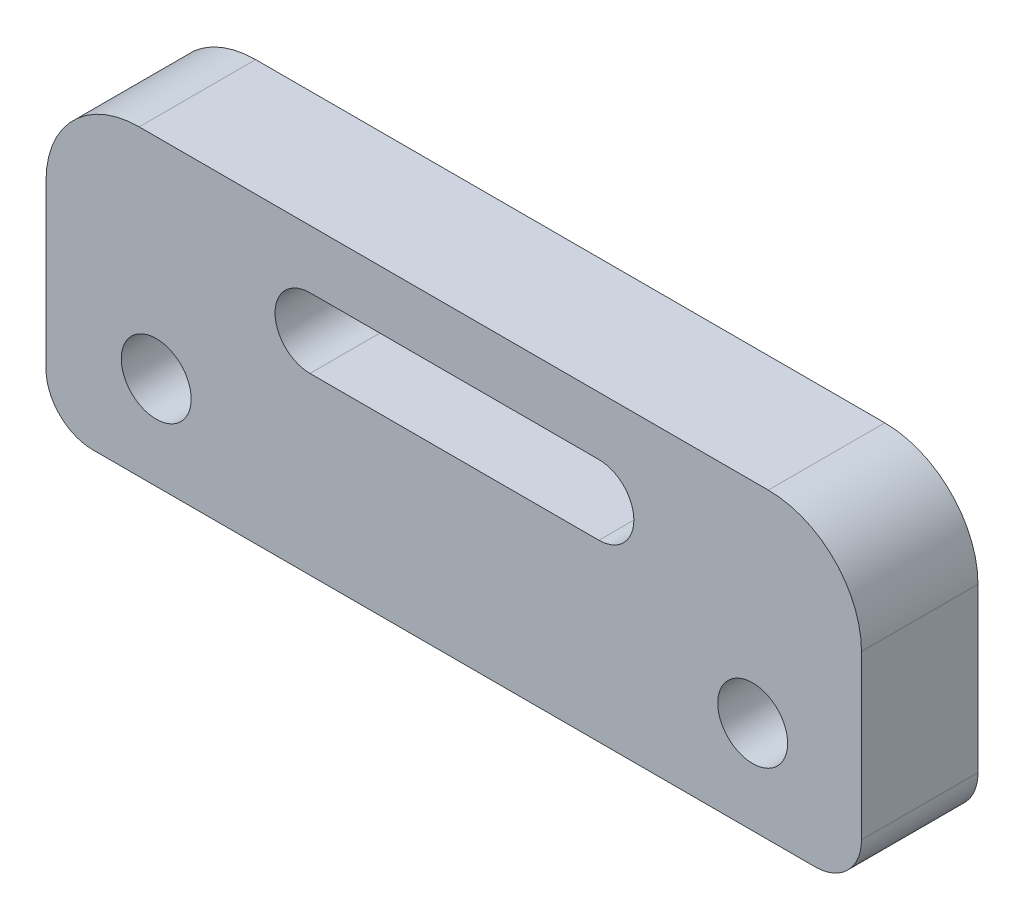
SolidWorks part; units mm, degrees
ref_plane "Plan de face" through (0, 0, 0) normal (0, 0, 1) x (1, 0, 0)
ref_plane "Plan de dessus" through (0, 0, 0) normal (0, 1, 0) x (1, 0, 0)
ref_plane "Plan de droite" through (0, 0, 0) normal (1, 0, 0) x (0, 0, -1)
sketch "Esquisse1" plane through (0, 0, 0) normal (0, 0, 1) x (1, 0, 0)
  line L0 (18.2524, -3.5802) -> (18.2524, 3.4198)
  line L1 (-12.7476, 7.4198) -> (14.2524, 7.4198)
  line L2 (0.7824, -5.5802) -> (0.7824, 14.0991) construction
  line L3 (-14.7476, -5.5802) -> (16.3124, -5.5802)
  line L4 (-16.7476, 3.4198) -> (-16.7476, -3.5802)
  line L5 (-5.4176, 1.9198) -> (6.9824, 1.9198)
  line L6 (6.9824, 4.9198) -> (-5.4176, 4.9198)
  arc A0 (16.3124, -5.5802) -> (18.2524, -3.5802) centre (16.2524, -3.5811) ccw
  arc A1 (-16.7476, -3.5802) -> (-14.7476, -5.5802) centre (-14.7476, -3.5802) ccw
  arc A2 (18.2524, 3.4198) -> (14.2524, 7.4198) centre (14.2524, 3.4198) ccw
  arc A3 (-12.7476, 7.4198) -> (-16.7476, 3.4198) centre (-12.7476, 3.4198) ccw
  circle A4 centre (13.5824, -1.5802) radius 1.5
  circle A5 centre (-12.0176, -1.5802) radius 1.5
  arc A6 (-5.4176, 4.9198) -> (-5.4176, 1.9198) centre (-5.4176, 3.4198) ccw
  arc A9 (6.9824, 1.9198) -> (6.9824, 4.9198) centre (6.9824, 3.4198) ccw
  dimension "D1" = 4
  dimension "D2" = 4
  dimension "D3" = 2
  dimension "D4" = 2
  dimension "D8" = 3
  dimension "D12" = 12.8
  dimension "D13" = 12.8
  dimension "D5" = 13
  dimension "D6" = 35
  dimension "D7" = 12.4
  dimension "D9" = 6.2
  dimension "D10" = 2.5
  dimension "D11" = 9
extrude "Boss.-Extru.1" add sketch "Esquisse1" along normal blind 5
